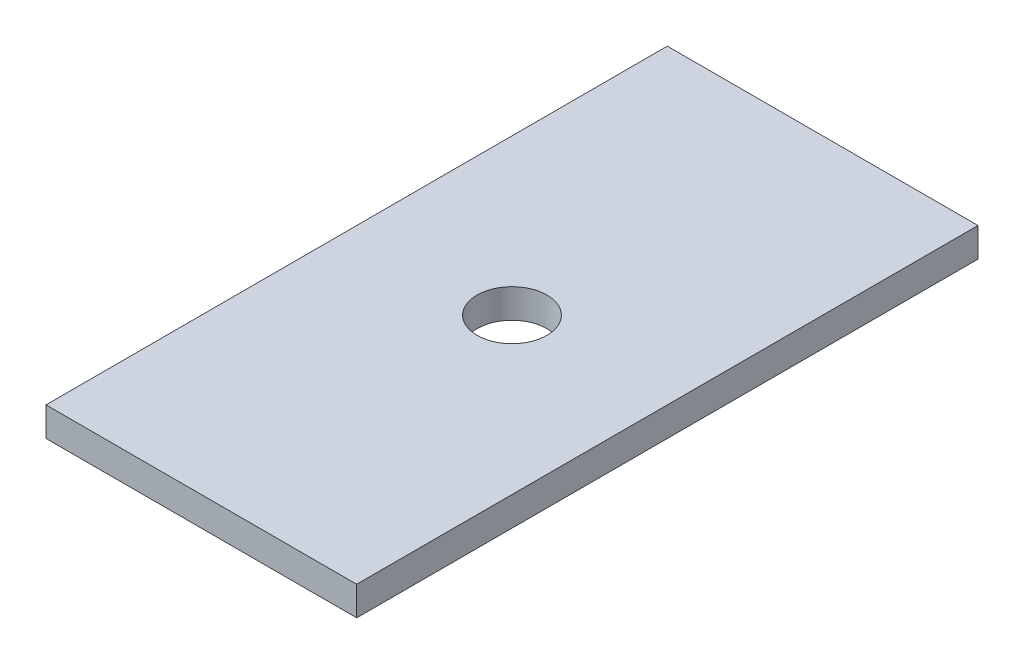
SolidWorks part; units mm, degrees
material "Pine"
ref_plane "Front Plane" through (0, 0, 0) normal (0, 0, 1) x (1, 0, 0)
ref_plane "Top Plane" through (0, 0, 0) normal (0, 1, 0) x (1, 0, 0)
ref_plane "Right Plane" through (0, 0, 0) normal (1, 0, 0) x (0, 0, -1)
sketch "Sketch1" plane through (0, 0, 0) normal (0, 1, 0) x (1, 0, 0)
  line L0 (38.1, 88.9) -> (38.1, 0) construction
  line L1 (0, 0) -> (127, 0)
  line L2 (0, 0) -> (0, 88.9)
  line L3 (0, 88.9) -> (127, 88.9)
  line L4 (127, 0) -> (127, 88.9)
  line L5 (63.5, 88.9) -> (63.5, 0) construction
  line L6 (88.9, 88.9) -> (88.9, 0) construction
  circle A0 centre (63.5, 44.45) radius 14.2875
  dimension "D2" = 28.575
  dimension "D3" = 38.1
  dimension "D5" = 11.1125
  dimension "D1" = 88.9
  dimension "D4" = 127
extrude "Boss-Extrude1" add sketch "Sketch1" along normal blind 11.9062
sketch "Sketch2" plane through (0, 11.9062, 0) normal (0, 1, 0) x (1, 0, 0)
  line L1 (0, 88.9) -> (127, 88.9)
  line L2 (0, 88.9) -> (0, 171.45)
  line L3 (0, 171.45) -> (127, 171.45)
  line L4 (127, 88.9) -> (127, 171.45)
  line L5 (127, 0) -> (0, 0)
  line L6 (127, 0) -> (127, -82.55)
  line L7 (127, -82.55) -> (0, -82.55)
  line L8 (0, 0) -> (0, -82.55)
  dimension "D1" = 82.55
  dimension "D3" = 254
extrude "Boss-Extrude2" add sketch "Sketch2" against normal up to surface (11.9062 mm away) up to face at (63.5, 0, -44.45)
